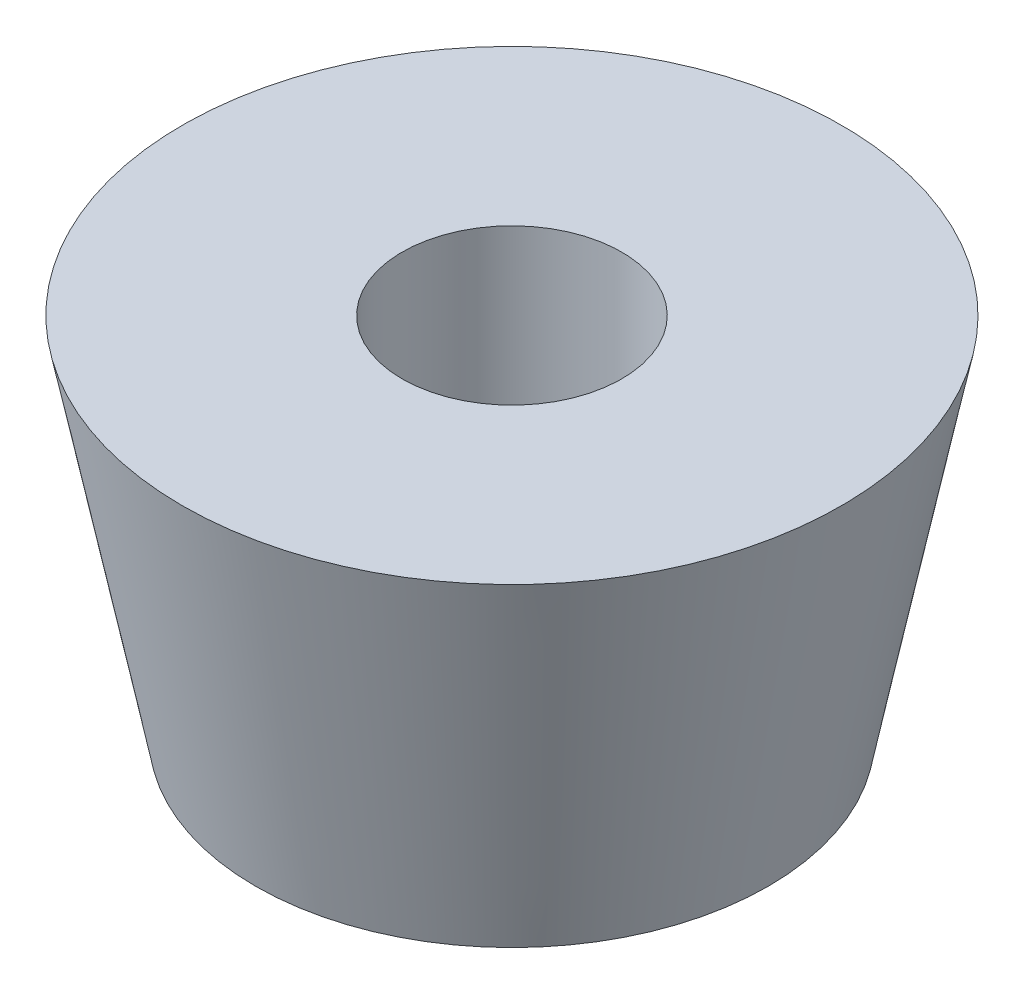
SolidWorks part; units mm, degrees
ref_plane "Front Plane" through (0, 0, 0) normal (0, 0, 1) x (1, 0, 0)
ref_plane "Top Plane" through (0, 0, 0) normal (0, 1, 0) x (1, 0, 0)
ref_plane "Right Plane" through (0, 0, 0) normal (1, 0, 0) x (0, 0, -1)
sketch "Sketch2" plane through (0, 0, 0) normal (1, 0, 0) x (0, 0, -1)
  line L0 (1.5, 0) -> (1.5, -5)
  line L1 (0, 0) -> (0, -5) construction
  line L2 (1.5, -5) -> (3.5, -5)
  line L3 (3.5, -5) -> (4.5, 0)
  line L4 (4.5, 0) -> (1.5, 0)
  dimension "D1" = 5
  dimension "D2" = 1.5
  dimension "D3" = 2
  dimension "D4" = 3
revolve "Revolve1" add sketch "Sketch2" angle 360 about L1
